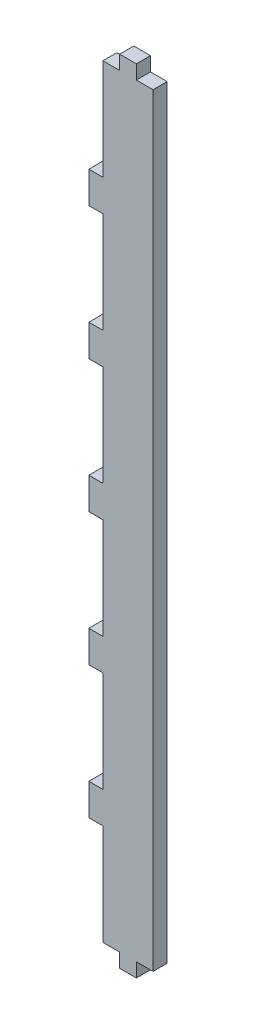
SolidWorks part; units mm, degrees
ref_plane "Front Plane" through (0, 0, 0) normal (0, 0, 1) x (1, 0, 0)
ref_plane "Top Plane" through (0, 0, 0) normal (0, 1, 0) x (1, 0, 0)
ref_plane "Right Plane" through (0, 0, 0) normal (1, 0, 0) x (0, 0, -1)
sketch "Model" plane through (0, 0, 0) normal (0, 0, 1) x (1, 0, 0)
  line L92 (24.4, 295.35) -> (18.05, 295.35)
  line L93 (24.4, 5.35) -> (24.4, 295.35)
  line L94 (18.05, 5.35) -> (24.4, 5.35)
  line L95 (18.05, 0) -> (18.05, 5.35)
  line L96 (11.7, 0) -> (18.05, 0)
  line L97 (11.7, 5.35) -> (11.7, 0)
  line L98 (5.35, 5.35) -> (11.7, 5.35)
  line L99 (5.35, 43.6833) -> (5.35, 5.35)
  line L100 (0, 43.6833) -> (5.35, 43.6833)
  line L101 (0, 55.6833) -> (0, 43.6833)
  line L102 (5.35, 55.6833) -> (0, 55.6833)
  line L103 (5.35, 94.0167) -> (5.35, 55.6833)
  line L104 (0, 94.0167) -> (5.35, 94.0167)
  line L105 (0, 106.0167) -> (0, 94.0167)
  line L106 (5.35, 106.0167) -> (0, 106.0167)
  line L107 (5.35, 144.35) -> (5.35, 106.0167)
  line L108 (0, 144.35) -> (5.35, 144.35)
  line L109 (0, 156.35) -> (0, 144.35)
  line L110 (5.35, 156.35) -> (0, 156.35)
  line L111 (5.35, 194.6833) -> (5.35, 156.35)
  line L112 (0, 194.6833) -> (5.35, 194.6833)
  line L113 (0, 206.6833) -> (0, 194.6833)
  line L114 (5.35, 206.6833) -> (0, 206.6833)
  line L115 (5.35, 245.0167) -> (5.35, 206.6833)
  line L116 (0, 245.0167) -> (5.35, 245.0167)
  line L117 (0, 257.0167) -> (0, 245.0167)
  line L118 (5.35, 257.0167) -> (0, 257.0167)
  line L119 (5.35, 295.35) -> (5.35, 257.0167)
  line L120 (11.7, 295.35) -> (5.35, 295.35)
  line L121 (11.7, 300.7) -> (11.7, 295.35)
  line L122 (18.05, 300.7) -> (11.7, 300.7)
  line L123 (18.05, 295.35) -> (18.05, 300.7)
extrude "Boss-Extrude1" add sketch "Model" along normal blind 5.35
